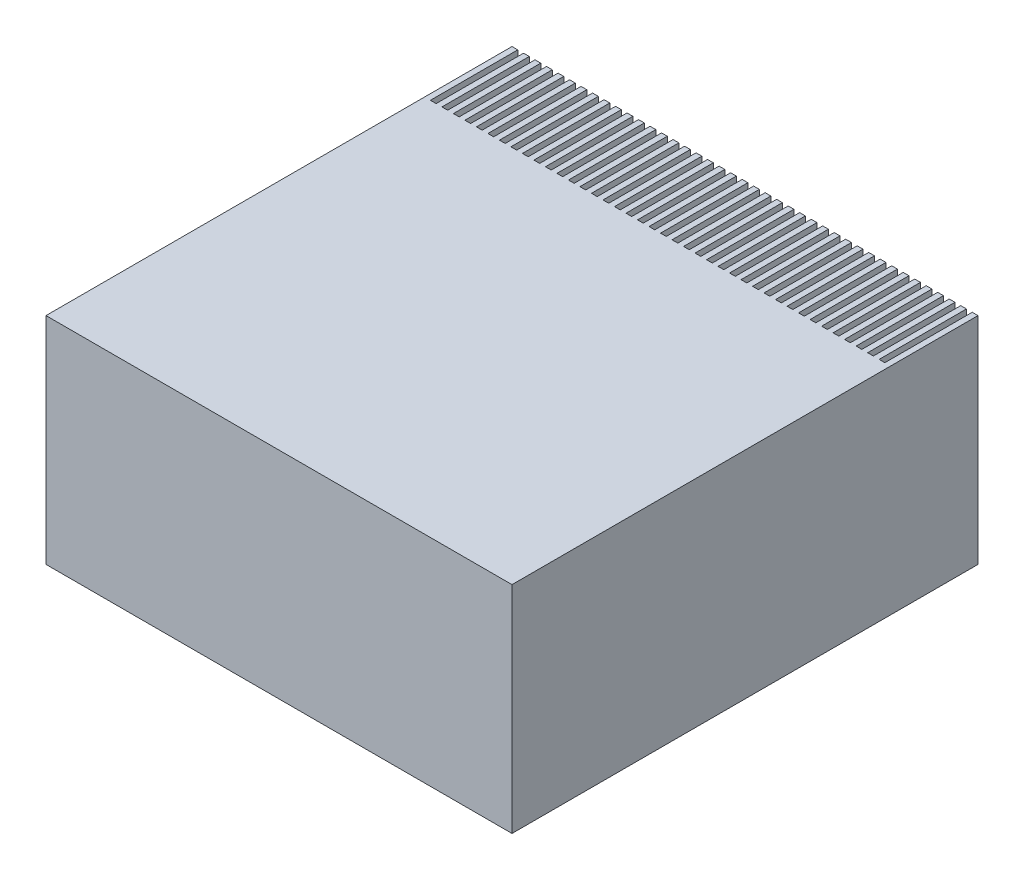
SolidWorks part; units mm, degrees
material "3.0205 (EN-AW 1200)"
ref_plane "Plan de face" through (0, 0, 0) normal (0, 0, 1) x (1, 0, 0)
ref_plane "Plan de dessus" through (0, 0, 0) normal (0, 1, 0) x (1, 0, 0)
ref_plane "Plan de droite" through (0, 0, 0) normal (1, 0, 0) x (0, 0, -1)
sketch "Sketch1" plane through (0, 0, 0) normal (0, 1, 0) x (1, 0, 0)
  line L1 (0, 0) -> (80, 0)
  line L2 (0, 0) -> (0, 80)
  line L3 (0, 80) -> (80, 80)
  line L4 (80, 0) -> (80, 80)
  dimension "D1" = 80
  dimension "D2" = 80
extrude "Extrude1" add sketch "Sketch1" along normal blind 37
sketch "Esquisse1" plane through (0, 0, -80) normal (0, 0, 1) x (1, 0, 0)
  line L0 (0, 37) -> (80, 37) construction
  line L1 (0.9877, 37) -> (1.9753, 37)
  line L2 (0.9877, 37) -> (0.9877, 0)
  line L3 (0.9877, 0) -> (1.9753, 0)
  line L4 (1.9753, 37) -> (1.9753, 0)
  line L5 (0, 0) -> (80, 0) construction
  line L6 (0, 37) -> (0, 0) construction
  dimension "D1" = 0.9877
  dimension "D2" = 0.9877
extrude "Enlèv. mat.-Extru.1" cut sketch "Esquisse1" along normal blind 15
pattern_linear "Répétition linéaire1" count 40 spacing 1.9753 along (1, 0, 0) of "Enlèv. mat.-Extru.1"
